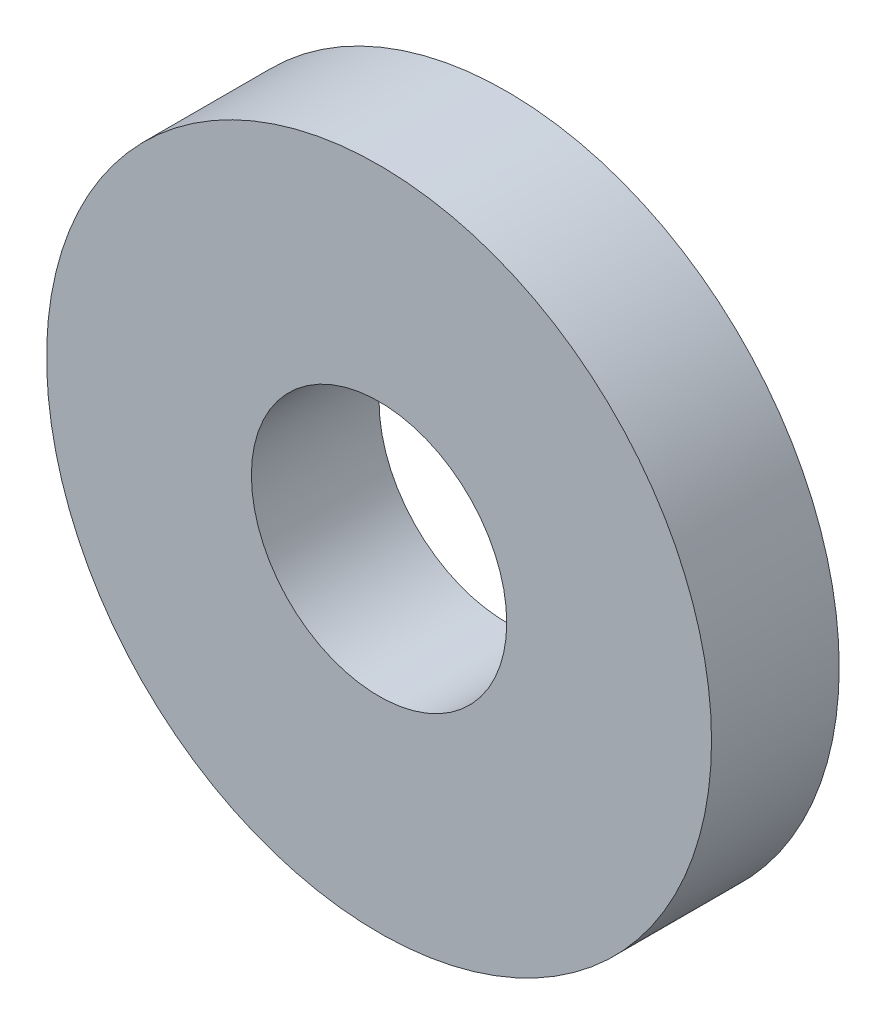
SolidWorks part; units mm, degrees
material "6061-T6 (SS)"
ref_plane "Front Plane" through (0, 0, 0) normal (0, 0, 1) x (1, 0, 0)
ref_plane "Top Plane" through (0, 0, 0) normal (0, 1, 0) x (1, 0, 0)
ref_plane "Right Plane" through (0, 0, 0) normal (1, 0, 0) x (0, 0, -1)
sketch "Sketch1" plane through (0, 0, 0) normal (0, 0, 1) x (1, 0, 0)
  circle A0 centre (-21, 0) radius 1.5875
  circle A1 centre (-21, 0) radius 4.1337
extrude "Boss-Extrude1" add sketch "Sketch1" along normal blind 1.5875
